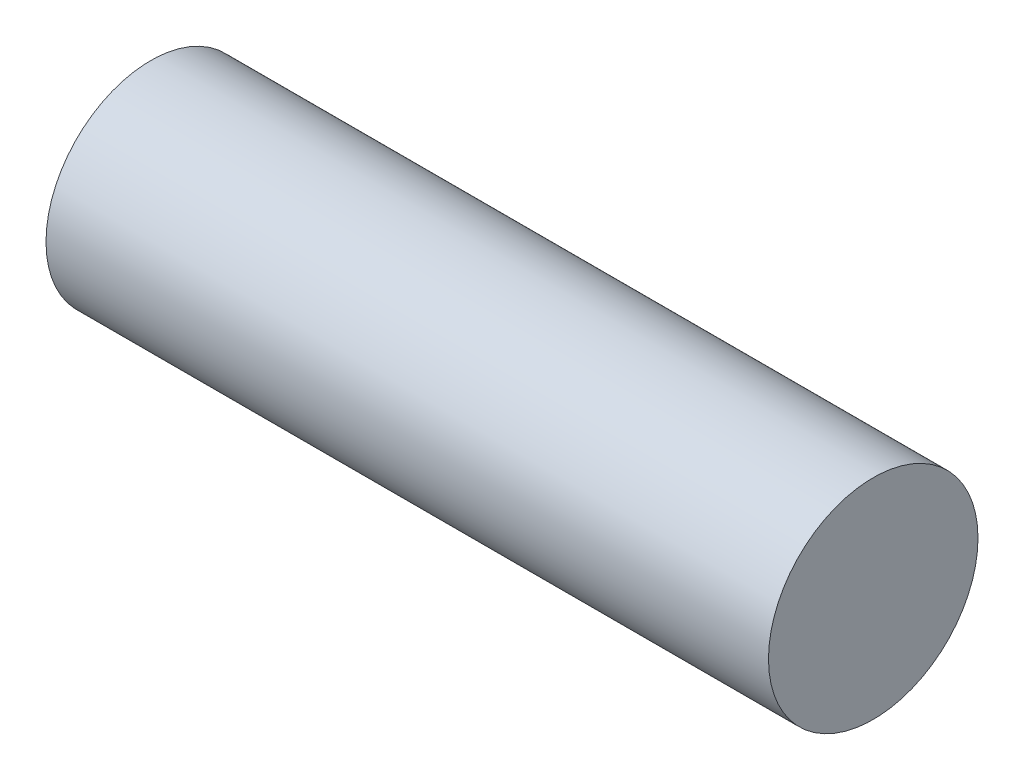
SolidWorks part; units mm, degrees
ref_plane "Front Plane" through (0, 0, 0) normal (0, 0, 1) x (1, 0, 0)
ref_plane "Top Plane" through (0, 0, 0) normal (0, 1, 0) x (1, 0, 0)
ref_plane "Right Plane" through (0, 0, 0) normal (1, 0, 0) x (0, 0, -1)
sketch "Sketch1" plane through (0, 0, 0) normal (1, 0, 0) x (0, 0, -1)
  circle A0 centre (0, 0) radius 7.25
  dimension "D1" = 14.5
extrude "Boss-Extrude1" add sketch "Sketch1" along normal mid plane 50
